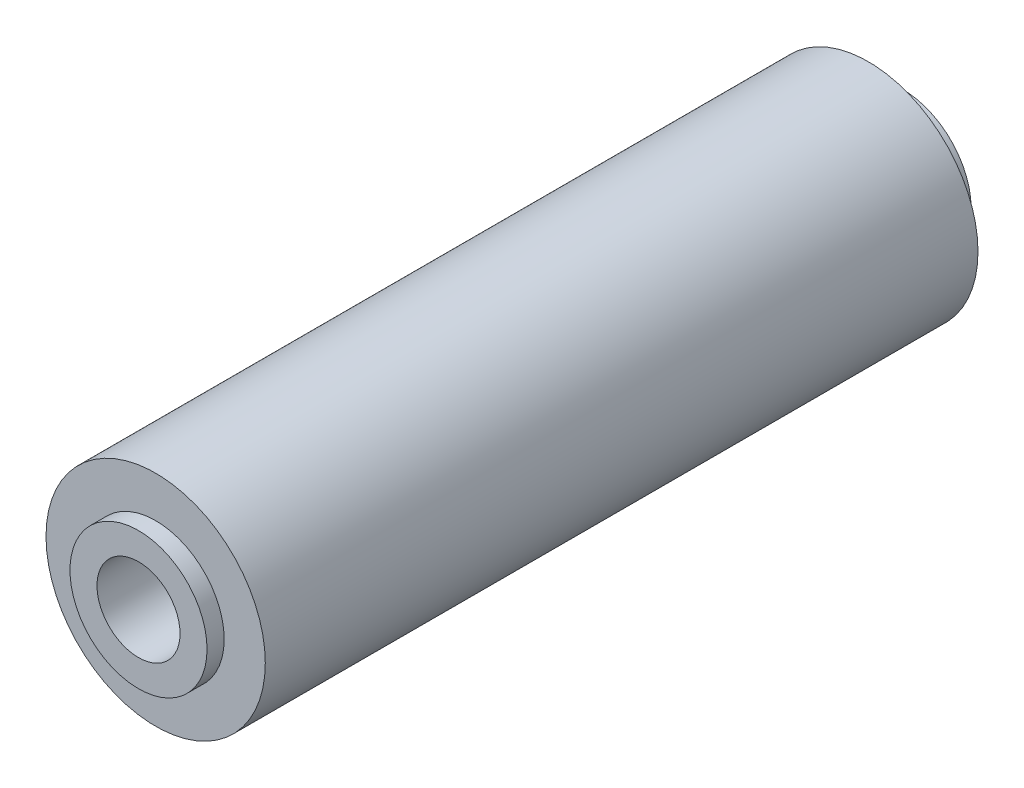
SolidWorks part; units mm, degrees
ref_plane "Front Plane" through (0, 0, 0) normal (0, 0, 1) x (1, 0, 0)
ref_plane "Top Plane" through (0, 0, 0) normal (0, 1, 0) x (1, 0, 0)
ref_plane "Right Plane" through (0, 0, 0) normal (1, 0, 0) x (0, 0, -1)
sketch "S01 - Turned steel body" plane through (0, 0, 0) normal (0, 0, 1) x (1, 0, 0)
  circle A0 centre (0, 0) radius 8
  dimension "D1" = 16
extrude "01 - Turned steel body" add sketch "S01 - Turned steel body" along normal blind 52
sketch "S02 - Backplate locating spigot" plane through (0, 0, 0) normal (0, 0, 1) x (1, 0, 0)
  circle A0 centre (0, 0) radius 5
  dimension "D1" = 10
extrude "02 - Backplate locating spigot" add sketch "S02 - Backplate locating spigot" along normal blind 2.5 from offset 2.5
sketch "S03 - Track locating spigot" plane through (0, 0, 0) normal (0, 0, 1) x (1, 0, 0)
  circle A0 centre (0, 0) radius 5
  dimension "D1" = 10
extrude "03 - Track locating spigot" add sketch "S03 - Track locating spigot" along normal blind 1.25 from offset 52
sketch "S04 - Rear M6 threaded envelope" plane through (0, 0, 0) normal (0, 0, 1) x (1, 0, 0)
  circle A0 centre (0, 0) radius 3.03
  dimension "D1" = 6.06
extrude "04 - Rear M6 threaded envelope" cut sketch "S04 - Rear M6 threaded envelope" along normal blind 14.1 from offset 2.6 offset against normal yes
sketch "S05 - Front M6 threaded envelope" plane through (0, 0, 0) normal (0, 0, 1) x (1, 0, 0)
  circle A0 centre (0, 0) radius 3.03
  dimension "D1" = 6.06
extrude "05 - Front M6 threaded envelope" cut sketch "S05 - Front M6 threaded envelope" along normal blind 15 from offset 38.5
